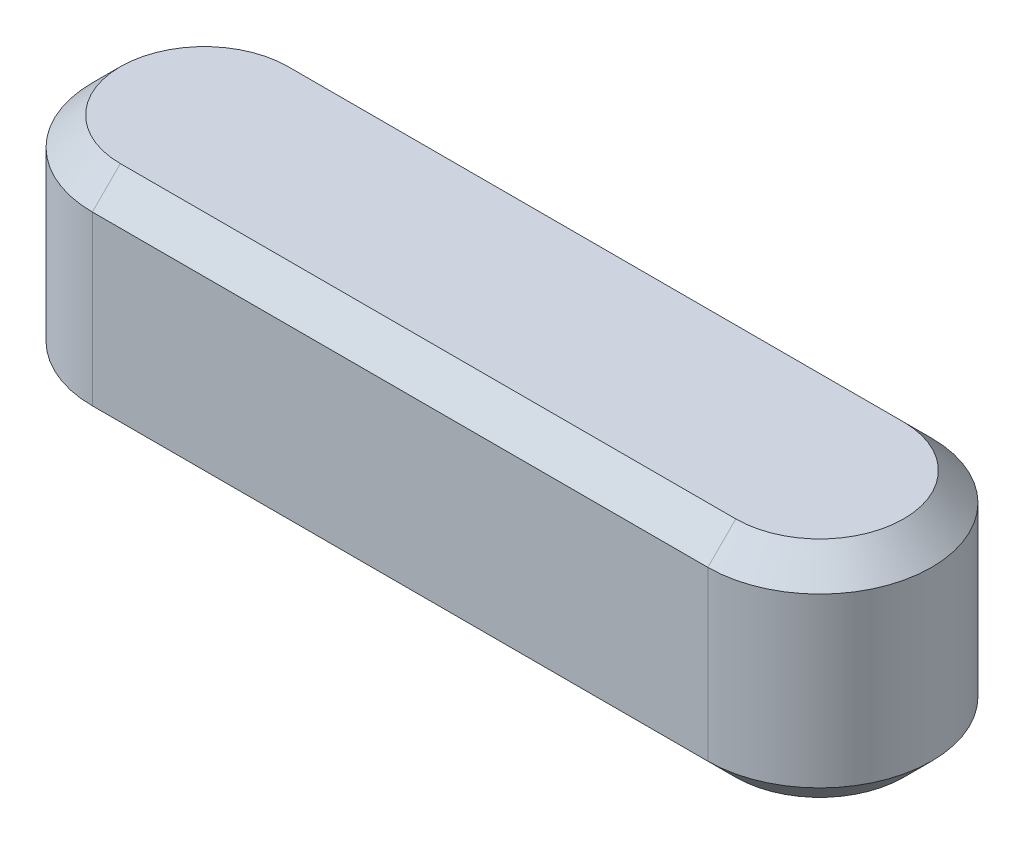
SolidWorks part; units mm, degrees
ref_plane "Front Plane" through (0, 0, 0) normal (0, 0, 1) x (1, 0, 0)
ref_plane "Top Plane" through (0, 0, 0) normal (0, 1, 0) x (1, 0, 0)
ref_plane "Right Plane" through (0, 0, 0) normal (1, 0, 0) x (0, 0, -1)
sketch "Sketch1" plane through (0, 0, 0) normal (0, 1, 0) x (1, 0, 0)
  line L0 (-5.5, 2) -> (5.5, 2)
  line L1 (0, 0) -> (14.7755, 0) construction
  line L2 (0, 0) -> (0, 8.6939) construction
  line L3 (-5.5, -2) -> (5.5, -2)
  arc A0 (5.5, 2) -> (5.5, -2) centre (5.5, 0) cw
  arc A1 (-5.5, 2) -> (-5.5, -2) centre (-5.5, 0) ccw
  point P10 (0, -2)
  point P12 (0, 2)
  dimension "D2" = 11
  dimension "D1" = 4
extrude "Boss-Extrude1" add sketch "Sketch1" along normal blind 4
chamfer "Chamfer1" distance 0.5 angle 45 8 edges at (-7.5, 0, 0) (0, 0, 2) (0, 0, -2) (7.5, 0, 0) (7.5, 4, 0) (0, 4, 2) (0, 4, -2) (-7.5, 4, 0)
